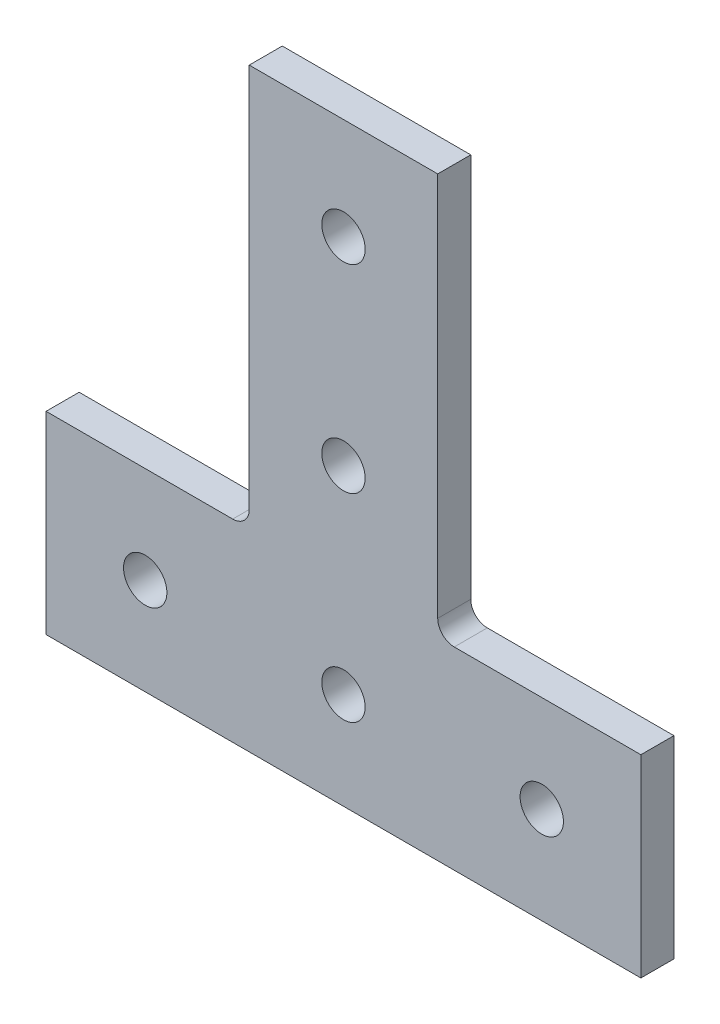
SolidWorks part; units mm, degrees
ref_plane "Front Plane" through (0, 0, 0) normal (0, 0, 1) x (1, 0, 0)
ref_plane "Top Plane" through (0, 0, 0) normal (0, 1, 0) x (1, 0, 0)
ref_plane "Right Plane" through (0, 0, 0) normal (1, 0, 0) x (0, 0, -1)
sketch "Sketch1" plane through (0, 0, 0) normal (0, 0, 1) x (1, 0, 0)
  line L0 (0, 57.15) -> (0, -57.15) construction
  line L1 (-57.15, -57.15) -> (57.15, -57.15) construction
  line L2 (57.15, -57.15) -> (57.15, -19.9898) construction
  line L3 (38.1, -34.4043) -> (38.1, -42.7355) construction
  line L4 (18.1102, 57.15) -> (-18.1102, 57.15) construction
  point P0 (0, -0.4699)
  point P4 (0, 0)
  point P8 (0, -57.15)
  point P11 (38.1, -38.5699)
  point P12 (57.15, -38.5699)
  point P15 (0, 57.15)
  dimension "Length" = 114.3
  dimension "Width1" = 37.1602
  dimension "Hole Dia" = 8.3312
  dimension "Hole to Edge" = 19.05
  dimension "Hole Spacing" = 38.1
  dimension "Width2" = 36.2204
sketch "Sketch2" plane through (0, 0, 0) normal (1, 0, 0) x (0, 0, -1)
  line L0 (3.175, 0) -> (-3.175, 0) construction
  point P4 (0, 0)
  dimension "Thickness" = 6.35
sketch "Sketch3" plane through (0, 0, 0) normal (0, 0, 1) x (1, 0, 0)
  line L0 (57.15, -57.15) -> (-57.15, -57.15)
  line L1 (57.15, -57.15) -> (57.15, -19.9898)
  line L2 (57.15, -19.9898) -> (21.2852, -19.9898)
  line L3 (18.1102, -16.8148) -> (18.1102, 57.15)
  line L4 (18.1102, 57.15) -> (-18.1102, 57.15)
  line L5 (18.1102, 57.15) -> (-18.1102, 57.15) construction
  line L6 (-57.15, -57.15) -> (57.15, -57.15) construction
  line L7 (0, -57.15) -> (0, 57.15) construction
  line L8 (-18.1102, -16.8148) -> (-18.1102, 57.15)
  line L9 (-57.15, -19.9898) -> (-21.2852, -19.9898)
  line L10 (-57.15, -57.15) -> (-57.15, -19.9898)
  arc A0 (-18.1102, -16.8148) -> (-21.2852, -19.9898) centre (-21.2852, -16.8148) cw
  arc A1 (21.2852, -19.9898) -> (18.1102, -16.8148) centre (21.2852, -16.8148) cw
  point P20 (-18.1102, -19.9898)
  point P23 (18.1102, -19.9898)
  dimension "Radius" = 3.175
extrude "Boss-Extrude1" add sketch "Sketch3" against normal up to vertex (3.175 mm away) and the other way up to vertex (3.175 mm away) up to point (0, 0, -3.175) other way up to point (0, 0, 3.175)
sketch "Sketch4" plane through (0, 0, 3.175) normal (0, 0, 1) x (1, 0, 0)
  line L0 (38.1, -34.4043) -> (38.1, -42.7355) construction
  line L1 (0, 57.15) -> (0, -57.15) construction
  line L2 (0, -57.15) -> (0, 57.15) construction
  line L3 (-57.15, -57.15) -> (57.15, -57.15) construction
  line L4 (0, -0.4699) -> (-18.1102, -0.4699) construction
  line L5 (-18.1102, 57.15) -> (-18.1102, -16.8148) construction
  circle A0 centre (38.1, -38.5699) radius 4.1656
  circle A1 centre (0, -38.5699) radius 4.1656
  circle A2 centre (-38.1, -38.5699) radius 4.1656
  circle A3 centre (0, -0.4699) radius 4.1656
  circle A4 centre (0, 37.6301) radius 4.1656
extrude "Cut-Extrude1" cut sketch "Sketch4" against normal through all
